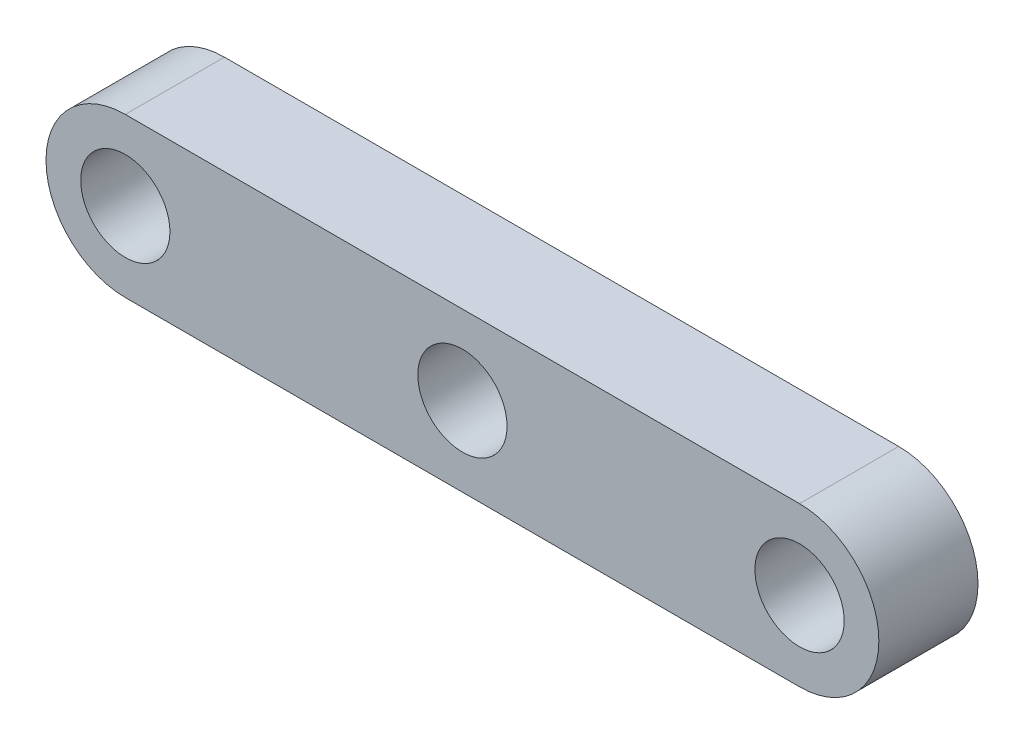
SolidWorks part; units mm, degrees
ref_plane "Front Plane" through (0, 0, 0) normal (0, 0, 1) x (1, 0, 0)
ref_plane "Top Plane" through (0, 0, 0) normal (0, 1, 0) x (1, 0, 0)
ref_plane "Right Plane" through (0, 0, 0) normal (1, 0, 0) x (0, 0, -1)
sketch "Sketch1" plane through (0, 0, 0) normal (0, 0, 1) x (1, 0, 0)
  line L0 (-17, 0) -> (17, 0) construction
  line L1 (-17, 4) -> (17, 4)
  line L2 (-17, -4) -> (17, -4)
  arc A0 (-17, 4) -> (-17, -4) centre (-17, 0) ccw
  arc A1 (17, -4) -> (17, 4) centre (17, 0) ccw
  circle A2 centre (0, 0) radius 2.25
  circle A3 centre (-17, 0) radius 2.25
  circle A4 centre (17, 0) radius 2.25
  point P3 (0, 0)
  point P14 (-15.3026, -6.35)
  dimension "D3" = 4.5
  dimension "D1" = 17
  dimension "D2" = 8
extrude "Boss-Extrude1" add sketch "Sketch1" along normal blind 5
